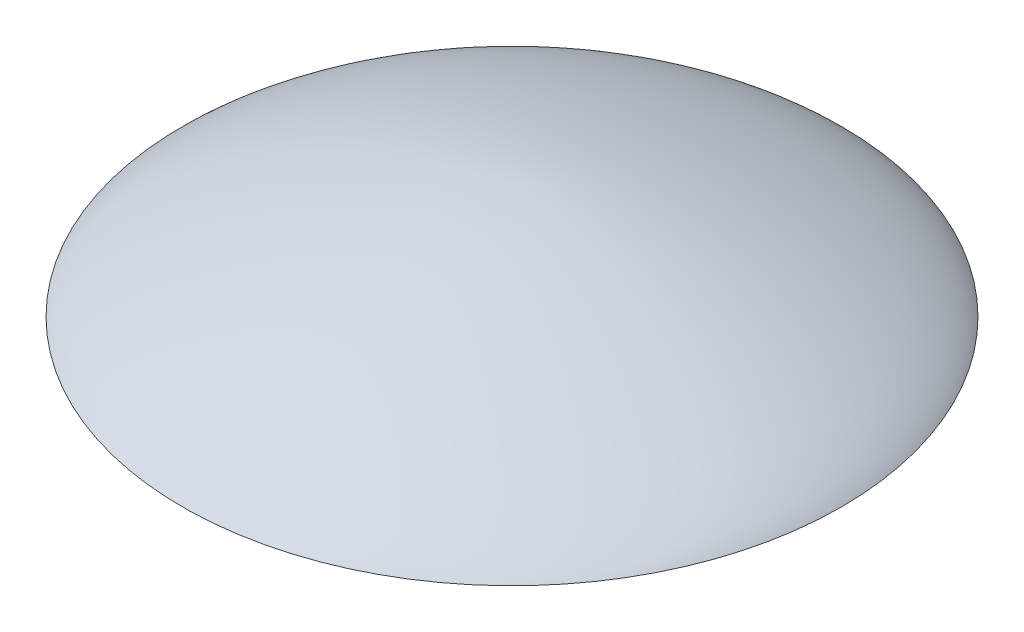
SolidWorks part; units mm, degrees
material "2014 Alloy"
ref_plane "Front Plane" through (0, 0, 0) normal (0, 0, 1) x (1, 0, 0)
ref_plane "Top Plane" through (0, 0, 0) normal (0, 1, 0) x (1, 0, 0)
ref_plane "Right Plane" through (0, 0, 0) normal (1, 0, 0) x (0, 0, -1)
sketch "Sketch1" plane through (0, 0, 0) normal (0, 0, 1) x (1, 0, 0)
  line L0 (0, -93.1542) -> (0, 93.1542) construction
  line L1 (115.4439, 0) -> (-115.4439, 0) construction
  line L3 (0, 20.7897) -> (0, 0)
  line L4 (0, 0) -> (67.5, 0)
  spline S0 degree 3 poles (67.5, 0) (60.0088, 7.5916) (21.0631, 21.76) (0, 20.7897) knots 0 0 0 0 1 1 1 1
  point P4 (0, 0)
  point P8 (0, 0)
  dimension "D1" = 67.5
revolve "Revolve1" add sketch "Sketch1" angle 360 about L0
